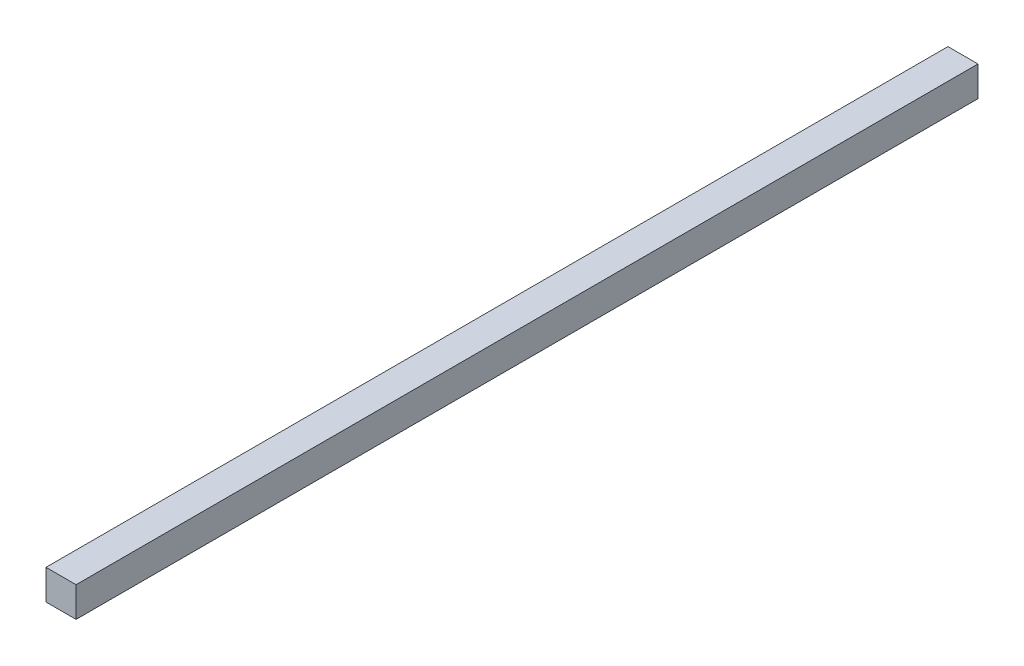
SolidWorks part; units mm, degrees
ref_plane "Front Plane" through (0, 0, 0) normal (0, 0, 1) x (1, 0, 0)
ref_plane "Top Plane" through (0, 0, 0) normal (0, 1, 0) x (1, 0, 0)
ref_plane "Right Plane" through (0, 0, 0) normal (1, 0, 0) x (0, 0, -1)
sketch "Sketch1" plane through (0, 0, 0) normal (0, 0, 1) x (1, 0, 0)
  line L1 (-2.5, -2.5) -> (2.5, -2.5)
  line L2 (-2.5, -2.5) -> (-2.5, 2.5)
  line L3 (-2.5, 2.5) -> (2.5, 2.5)
  line L4 (2.5, -2.5) -> (2.5, 2.5)
  line L5 (-2.5, -2.5) -> (2.5, 2.5) construction
  line L6 (-2.5, 2.5) -> (2.5, -2.5) construction
  point P0 (0, 0)
  dimension "D1" = 5
  dimension "D2" = 5
extrude "Boss-Extrude1" add sketch "Sketch1" along normal blind 150
